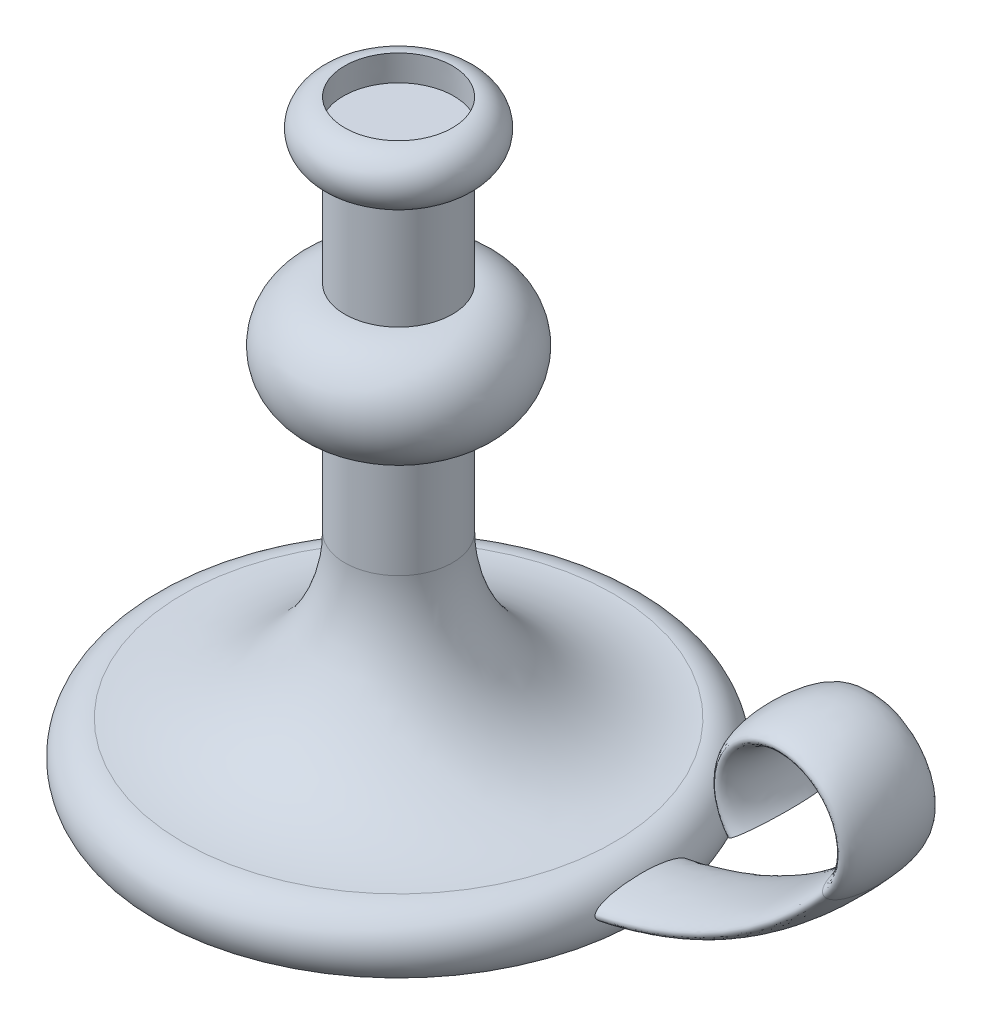
SolidWorks part; units mm, degrees
ref_plane "Front Plane" through (0, 0, 0) normal (0, 0, 1) x (1, 0, 0)
ref_plane "Top Plane" through (0, 0, 0) normal (0, 1, 0) x (1, 0, 0)
ref_plane "Right Plane" through (0, 0, 0) normal (1, 0, 0) x (0, 0, -1)
sketch "Sketch1" plane through (0, 0, 0) normal (0, 0, 1) x (1, 0, 0)
  line L0 (0, 0) -> (-90, 0)
  line L1 (-90, 0) -> (-90, 220)
  line L2 (-90, 220) -> (-70, 220)
  line L3 (-70, 200) -> (-70, 160)
  line L4 (-70, 120) -> (-70, 80)
  arc A0 (-70, 220) -> (-70, 200) centre (-70, 210) cw
  arc A1 (-70, 160) -> (-70, 120) centre (-70, 140) cw
  arc A2 (-70, 80) -> (-10, 20) centre (-10, 80) ccw
  arc A3 (-10, 20) -> (0, 0) centre (-10, 7.5) cw
  dimension "D4" = 10
  dimension "D6" = 20
  dimension "D8" = 60
  dimension "D9" = 12.5
  dimension "D1" = 90
  dimension "D2" = 220
  dimension "D3" = 20
  dimension "D5" = 40
  dimension "D7" = 80
revolve "Revolve1" add sketch "Sketch1" angle 360 about L1
sketch "Sketch2" plane through (0, 0, 0) normal (0, 0, 1) x (1, 0, 0)
  line L0 (-90, 10) -> (-30, 10)
  line L1 (-90, 200) -> (-90, 160) construction
  line L2 (-90, 227.4356) -> (-90, 175.1288) construction
  line L4 (-180, 0) -> (0, 0) construction
  arc A0 (-30, 10) -> (83.4941, 61.9231) centre (-30, 160) ccw
  arc A1 (83.4941, 61.9231) -> (53.229, 61.9231) centre (68.3616, 75) ccw
  point P8 (0, 0)
  point P11 (0, 0)
  point P14 (0, 0)
  dimension "D2" = 150
  dimension "D3" = 20
  dimension "D1" = 60
  dimension "D4" = 65
  dimension "D5" = 10
sketch "Sketch4" plane through (0, 0, 0) normal (1, 0, 0) x (0, 0, -1)
  ellipse E0 centre (0, 10) end of major axis (-17.5, 10) minor radius 5
  point P1 (0, 0)
  dimension "D1" = 10
  dimension "D2" = 35
sweep "Sweep1" add profiles "Sketch4" path "Sketch2"
sketch "Sketch5" plane through (0, 220, 0) normal (0, 1, 0) x (1, 0, 0)
  circle A0 centre (-90, 0) radius 20
extrude "Cut-Extrude1" cut sketch "Sketch5" against normal blind 10 draft 3 draft outward yes
